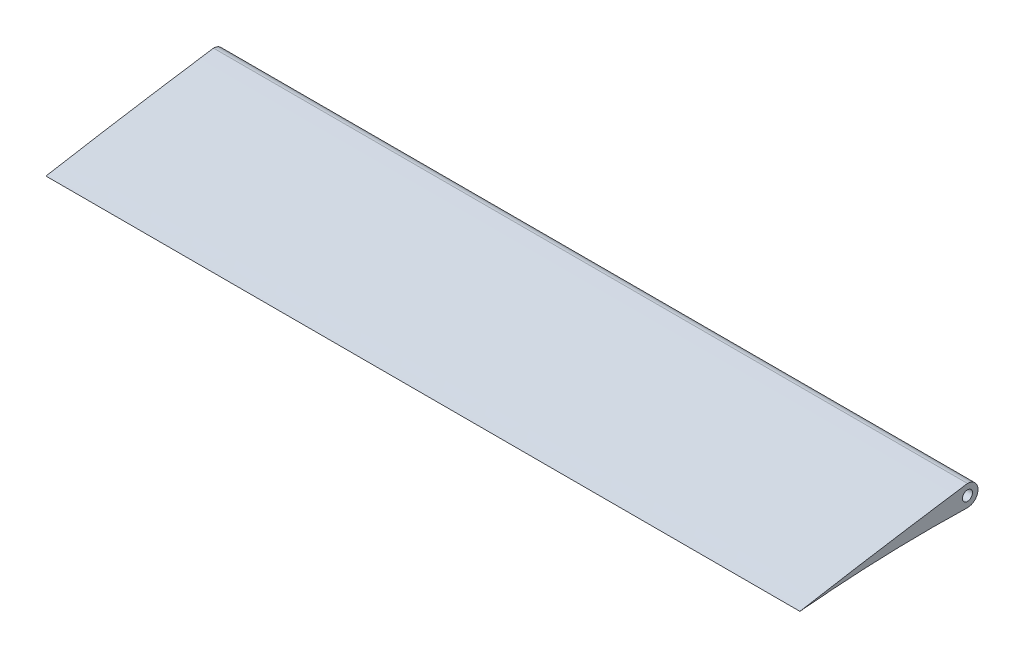
SolidWorks part; units mm, degrees
material "Foam"
ref_plane "Piano frontale" through (0, 0, 0) normal (0, 0, 1) x (1, 0, 0)
ref_plane "Piano superiore" through (0, 0, 0) normal (0, 1, 0) x (1, 0, 0)
ref_plane "Piano destro" through (0, 0, 0) normal (1, 0, 0) x (0, 0, -1)
curve "Curva1"
  spline degree 3 poles (0, 0.1724, 248.285) (0, -0.053, 250.4273) (0, 0.2462, 248.3284) (0, 0.5529, 246.6445) (0, 1.2459, 242.6221) (0, 2.0989, 237.7464) (0, 3.1818, 231.3634) (0, 4.2933, 223.9772) (0, 5.7312, 215.5604) (0, 7.1315, 206.3004) (0, 8.6324, 196.1631) (0, 10.1162, 185.3524) (0, 11.5493, 173.9891) (0, 12.8816, 162.1914) (0, 14.0593, 150.0724) (0, 15.0523, 137.7438) (0, 15.8256, 125.3116) (0, 16.3834, 112.8888) (0, 16.7267, 100.597) (0, 16.8648, 88.5669) (0, 16.792, 76.9314) (0, 16.4941, 65.8165) (0, 15.9609, 55.3329) (0, 15.1594, 45.573) (0, 14.0978, 36.6074) (0, 12.7884, 28.4972) (0, 11.2839, 21.2988) (0, 9.6413, 15.0749) (0, 7.9136, 9.8809) (0, 6.1182, 5.7699) (0, 4.2384, 2.7289) (0, 2.3057, 0.8126) (0, 0.7927, 0.0312) (0, -0.4105, -0.0213) (0, -1.7115, 0.4949) (0, -2.8658, 2.6253) (0, -4.0404, 5.6977) (0, -4.9287, 10.0719) (0, -5.5974, 15.6262) (0, -6.0122, 22.4122) (0, -6.265, 30.3619) (0, -6.3814, 39.3972) (0, -6.3554, 49.3987) (0, -6.2185, 60.2453) (0, -5.9476, 71.8018) (0, -5.5368, 83.9408) (0, -4.9386, 96.5461) (0, -4.1527, 109.5201) (0, -3.2196, 122.7671) (0, -2.1909, 136.1764) (0, -1.148, 149.6158) (0, -0.1602, 162.9314) (0, 0.706, 175.9537) (0, 1.3896, 188.4999) (0, 1.8332, 200.3712) (0, 1.9676, 211.3376) (0, 1.8232, 221.1842) (0, 1.4973, 229.6804) (0, 1.0741, 236.8065) (0, 0.6857, 242.1894) (0, 0.3087, 246.5181) (0, 0.1724, 248.285) (0, -0.053, 250.4273) (0, 0.2462, 248.3284) knots -0.014202 -0.006329 -0.001589 0 0.001576 0.006211 0.01368 0.023764 0.036307 0.051658 0.068045 0.086769 0.107053 0.128647 0.151303 0.174786 0.19886 0.223309 0.247929 0.272522 0.296848 0.320648 0.343669 0.365658 0.3864 0.405741 0.423561 0.439779 0.454311 0.467034 0.477831 0.486643 0.493542 0.498786 0.50271 0.50309 0.505896 0.510322 0.516831 0.525521 0.536535 0.549945 0.565696 0.583577 0.603379 0.624844 0.647727 0.671743 0.696673 0.722357 0.748609 0.77521 0.801891 0.828329 0.854175 0.879074 0.902636 0.924421 0.943939 0.960827 0.974827 0.985798 0.993671 0.998411 1 1.001576 1.006211 1.01368 periodic
sketch "Schizzo1" plane through (0, 0, 0) normal (1, 0, 0) x (0, 0, -1)
  line L0 (-250, 0) -> (-249.9688, 0) construction
  line L3 (-200, 8.0593) -> (-200, 1.7757) construction
  arc A1 (-200, 8.0593) -> (-200, 1.7757) centre (-200, 4.9175) cw
  circle A2 centre (-200, 4.9175) radius 1.5
  spline S1 degree 3 poles (-200, 8.0593) (-202.1874, 7.7398) (-207.5057, 6.9493) (-215.5604, 5.7312) (-223.9772, 4.2933) (-231.3634, 3.1818) (-237.7464, 2.0989) (-242.6221, 1.2459) (-246.6445, 0.5529) (-248.3284, 0.2462) (-250.4273, -0.053) (-248.285, 0.1724) (-246.5181, 0.3087) (-242.1894, 0.6857) (-236.8065, 1.0741) (-229.6804, 1.4973) (-221.1842, 1.8232) (-211.3376, 1.9676) (-204.1306, 1.8793) (-200.2242, 1.7814) (-200, 1.7757) knots 0.900158 0.900158 0.900158 0.900158 0.913231 0.931955 0.948342 0.963693 0.976236 0.98632 0.993789 0.998424 1 1.001589 1.006329 1.014202 1.025173 1.039173 1.056061 1.075579 1.097364 1.09869 1.09869 1.09869 1.09869
  spline S2 degree 3 poles (-248.3284, 0.2462) (-250.4273, -0.053) (-248.285, 0.1724) (-246.5181, 0.3087) (-242.1894, 0.6857) (-236.8065, 1.0741) (-229.6804, 1.4973) (-221.1842, 1.8232) (-211.3376, 1.9676) (-200.3712, 1.8332) (-188.4999, 1.3896) (-175.9537, 0.706) (-162.9314, -0.1602) (-149.6158, -1.148) (-136.1764, -2.1909) (-122.7671, -3.2196) (-109.5201, -4.1527) (-96.5461, -4.9386) (-83.9408, -5.5368) (-71.8018, -5.9476) (-60.2453, -6.2185) (-49.3987, -6.3554) (-39.3972, -6.3814) (-30.3619, -6.265) (-22.4122, -6.0122) (-15.6262, -5.5974) (-10.0719, -4.9287) (-5.6977, -4.0404) (-2.6253, -2.8658) (-0.4949, -1.7115) (0.0213, -0.4105) (-0.0312, 0.7927) (-0.8126, 2.3057) (-2.7289, 4.2384) (-5.7699, 6.1182) (-9.8809, 7.9136) (-15.0749, 9.6413) (-21.2988, 11.2839) (-28.4972, 12.7884) (-36.6074, 14.0978) (-45.573, 15.1594) (-55.3329, 15.9609) (-65.8165, 16.4941) (-76.9314, 16.792) (-88.5669, 16.8648) (-100.597, 16.7267) (-112.8888, 16.3834) (-125.3116, 15.8256) (-137.7438, 15.0523) (-150.0724, 14.0593) (-162.1914, 12.8816) (-173.9891, 11.5493) (-185.3524, 10.1162) (-196.1631, 8.6324) (-206.3004, 7.1315) (-215.5604, 5.7312) (-223.9772, 4.2933) (-231.3634, 3.1818) (-237.7464, 2.0989) (-242.6221, 1.2459) (-246.6445, 0.5529) (-248.3284, 0.2462) (-250.4273, -0.053) (-248.285, 0.1724) knots -0.01368 -0.006211 -0.001576 0 0.001589 0.006329 0.014202 0.025173 0.039173 0.056061 0.075579 0.097364 0.120926 0.145825 0.171671 0.198109 0.22479 0.251391 0.277643 0.303327 0.328257 0.352273 0.375156 0.396621 0.416423 0.434304 0.450055 0.463465 0.474479 0.483169 0.489678 0.494104 0.49691 0.49729 0.501214 0.506458 0.513357 0.522169 0.532966 0.545689 0.560221 0.576439 0.594259 0.6136 0.634342 0.656331 0.679352 0.703152 0.727478 0.752071 0.776691 0.80114 0.825214 0.848697 0.871353 0.892947 0.913231 0.931955 0.948342 0.963693 0.976236 0.98632 0.993789 0.998424 1 1.001589 1.006329 1.014202 only from (-250, 0) to (-250, 0) construction
  spline S3 degree 3 poles (-248.3284, 0.2462) (-250.4273, -0.053) (-248.285, 0.1724) (-246.5181, 0.3087) (-242.1894, 0.6857) (-236.8065, 1.0741) (-229.6804, 1.4973) (-221.1842, 1.8232) (-211.3376, 1.9676) (-200.3712, 1.8332) (-188.4999, 1.3896) (-175.9537, 0.706) (-162.9314, -0.1602) (-149.6158, -1.148) (-136.1764, -2.1909) (-122.7671, -3.2196) (-109.5201, -4.1527) (-96.5461, -4.9386) (-83.9408, -5.5368) (-71.8018, -5.9476) (-60.2453, -6.2185) (-49.3987, -6.3554) (-39.3972, -6.3814) (-30.3619, -6.265) (-22.4122, -6.0122) (-15.6262, -5.5974) (-10.0719, -4.9287) (-5.6977, -4.0404) (-2.6253, -2.8658) (-0.4949, -1.7115) (0.0213, -0.4105) (-0.0312, 0.7927) (-0.8126, 2.3057) (-2.7289, 4.2384) (-5.7699, 6.1182) (-9.8809, 7.9136) (-15.0749, 9.6413) (-21.2988, 11.2839) (-28.4972, 12.7884) (-36.6074, 14.0978) (-45.573, 15.1594) (-55.3329, 15.9609) (-65.8165, 16.4941) (-76.9314, 16.792) (-88.5669, 16.8648) (-100.597, 16.7267) (-112.8888, 16.3834) (-125.3116, 15.8256) (-137.7438, 15.0523) (-150.0724, 14.0593) (-162.1914, 12.8816) (-173.9891, 11.5493) (-185.3524, 10.1162) (-196.1631, 8.6324) (-206.3004, 7.1315) (-215.5604, 5.7312) (-223.9772, 4.2933) (-231.3634, 3.1818) (-237.7464, 2.0989) (-242.6221, 1.2459) (-246.6445, 0.5529) (-248.3284, 0.2462) (-250.4273, -0.053) (-248.285, 0.1724) knots -0.01368 -0.006211 -0.001576 0 0.001589 0.006329 0.014202 0.025173 0.039173 0.056061 0.075579 0.097364 0.120926 0.145825 0.171671 0.198109 0.22479 0.251391 0.277643 0.303327 0.328257 0.352273 0.375156 0.396621 0.416423 0.434304 0.450055 0.463465 0.474479 0.483169 0.489678 0.494104 0.49691 0.49729 0.501214 0.506458 0.513357 0.522169 0.532966 0.545689 0.560221 0.576439 0.594259 0.6136 0.634342 0.656331 0.679352 0.703152 0.727478 0.752071 0.776691 0.80114 0.825214 0.848697 0.871353 0.892947 0.913231 0.931955 0.948342 0.963693 0.976236 0.98632 0.993789 0.998424 1 1.001589 1.006329 1.014202 only from (-250, 0) to (-250, 0) construction
  dimension "D2" = 3
  dimension "D1" = 6.2836
  dimension "D7" = 50
extrude "CorpoFoam" add sketch "Schizzo1" along normal blind 225
